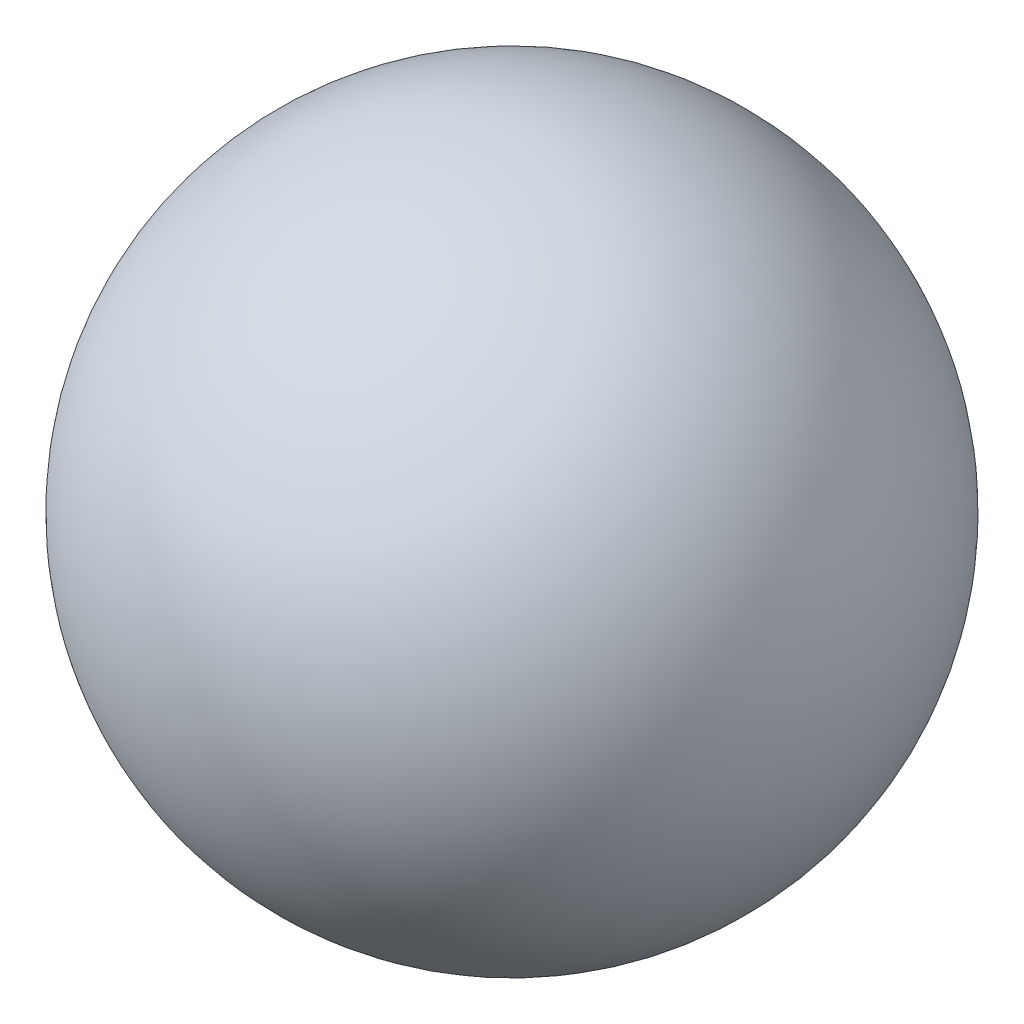
SolidWorks part; units mm, degrees
ref_plane "Front Plane" through (0, 0, 0) normal (0, 0, 1) x (1, 0, 0)
ref_plane "Top Plane" through (0, 0, 0) normal (0, 1, 0) x (1, 0, 0)
ref_plane "Right Plane" through (0, 0, 0) normal (1, 0, 0) x (0, 0, -1)
sketch "Sketch1" plane through (0, 0, 0) normal (0, 1, 0) x (1, 0, 0)
  line L0 (0, 9.0351) -> (0, -4.7625) construction
  line L1 (0, -4.7625) -> (0, 4.7625)
  arc A0 (0, 4.7625) -> (0, -4.7625) centre (0, 0) ccw
  dimension "D1" = 9.525
revolve "Revolve2" add sketch "Sketch1" angle 360 about L0
